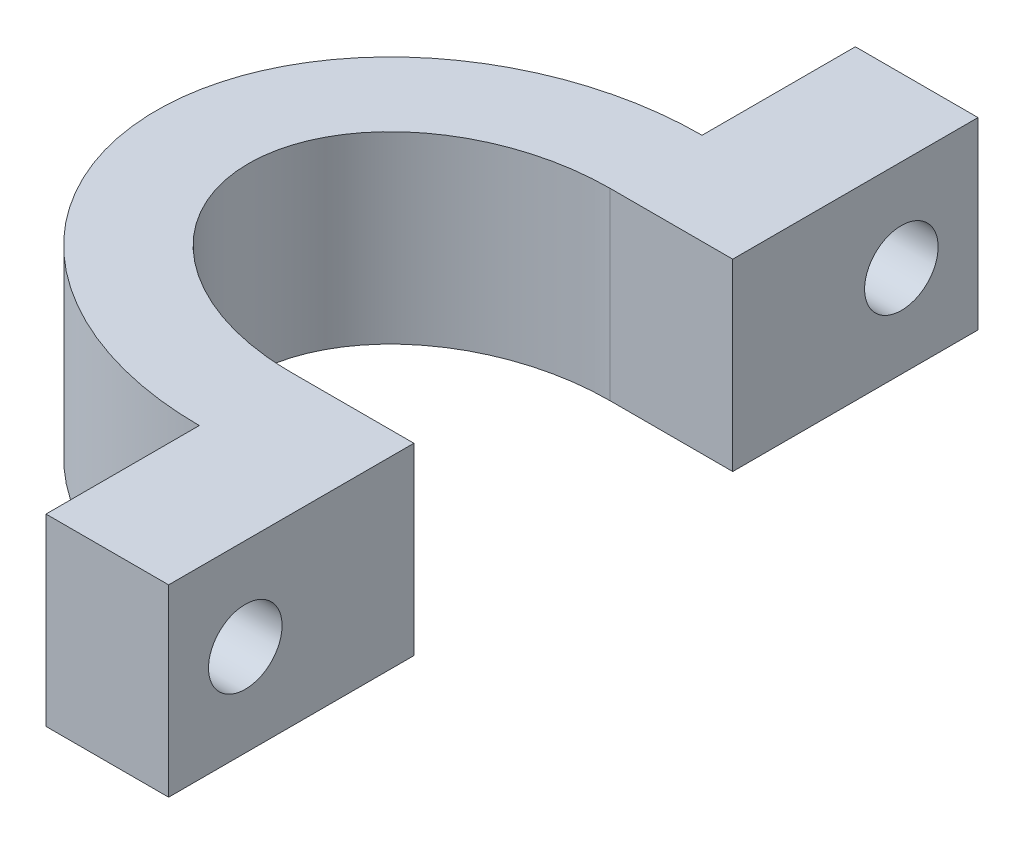
SolidWorks part; units mm, degrees
ref_plane "Front Plane" through (0, 0, 0) normal (0, 0, 1) x (1, 0, 0)
ref_plane "Top Plane" through (0, 0, 0) normal (0, 1, 0) x (1, 0, 0)
ref_plane "Right Plane" through (0, 0, 0) normal (1, 0, 0) x (0, 0, -1)
sketch "Sketch1" plane through (0, 0, 0) normal (0, 1, 0) x (1, 0, 0)
  line L0 (0, 20.5) -> (0, -20.5)
  ellipse E0 centre (0, 0) end of major axis (16.5, 0) minor radius 13
  ellipse E1 centre (0, 0) end of major axis (24, 0) minor radius 20.5
  dimension "D1" = 26
  dimension "D2" = 33
  dimension "D3" = 48
  dimension "D4" = 41
extrude "Boss-Extrude1" add sketch "Sketch1" along normal blind 15 contours L0 E1 E0
sketch "Sketch2" plane through (0, 0, 0) normal (1, 0, 0) x (0, 0, -1)
  line L0 (0, 0) -> (0, 15) construction
  line L1 (13, 15) -> (33, 15)
  line L2 (13, 15) -> (13, 0)
  line L3 (13, 0) -> (33, 0)
  line L4 (33, 15) -> (33, 0)
  line L5 (13, 15) -> (-13, 15) construction
  line L6 (-13, 0) -> (-33, 0)
  line L7 (-33, 15) -> (-33, 0)
  line L8 (-13, 15) -> (-33, 15)
  line L9 (-13, 15) -> (-13, 0)
  dimension "D1" = 20
extrude "Boss-Extrude2" add sketch "Sketch2" along normal blind 10
sketch "Sketch3" plane through (0, 0, 0) normal (-1, 0, 0) x (0, 0, 1)
  line L0 (-33, 15) -> (-20.5, 0) construction
  line L1 (-20.5, 15) -> (-33, 0) construction
  line L2 (0, 0) -> (0, 15) construction
  line L3 (20.5, 15) -> (-20.5, 15) construction
  circle A0 centre (-26.75, 7.5) radius 3
  circle A1 centre (26.75, 7.5) radius 3
  dimension "D1" = 6
extrude "Cut-Extrude1" cut sketch "Sketch3" against normal through all
